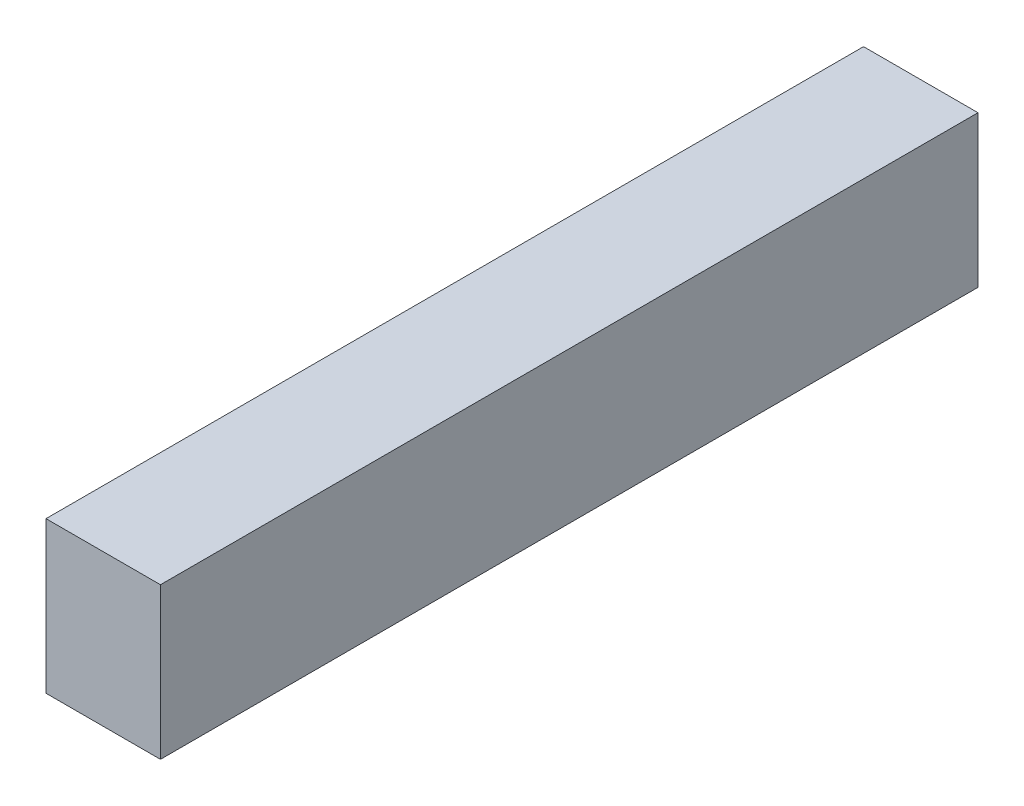
SolidWorks part; units mm, degrees
ref_plane "Front Plane" through (0, 0, 0) normal (0, 0, 1) x (1, 0, 0)
ref_plane "Top Plane" through (0, 0, 0) normal (0, 1, 0) x (1, 0, 0)
ref_plane "Right Plane" through (0, 0, 0) normal (1, 0, 0) x (0, 0, -1)
sketch "Sketch1" plane through (0, 0, 0) normal (0, 0, 1) x (1, 0, 0)
  line L1 (-1.778, 2.3495) -> (1.778, 2.3495)
  line L2 (-1.778, 2.3495) -> (-1.778, -2.3495)
  line L3 (-1.778, -2.3495) -> (1.778, -2.3495)
  line L4 (1.778, 2.3495) -> (1.778, -2.3495)
  line L5 (-1.778, 2.3495) -> (1.778, -2.3495) construction
  line L6 (-1.778, -2.3495) -> (1.778, 2.3495) construction
  point P0 (0, 0)
  dimension "D1" = 3.556
  dimension "D2" = 4.699
extrude "Extrude1" add sketch "Sketch1" against normal blind 25.4
